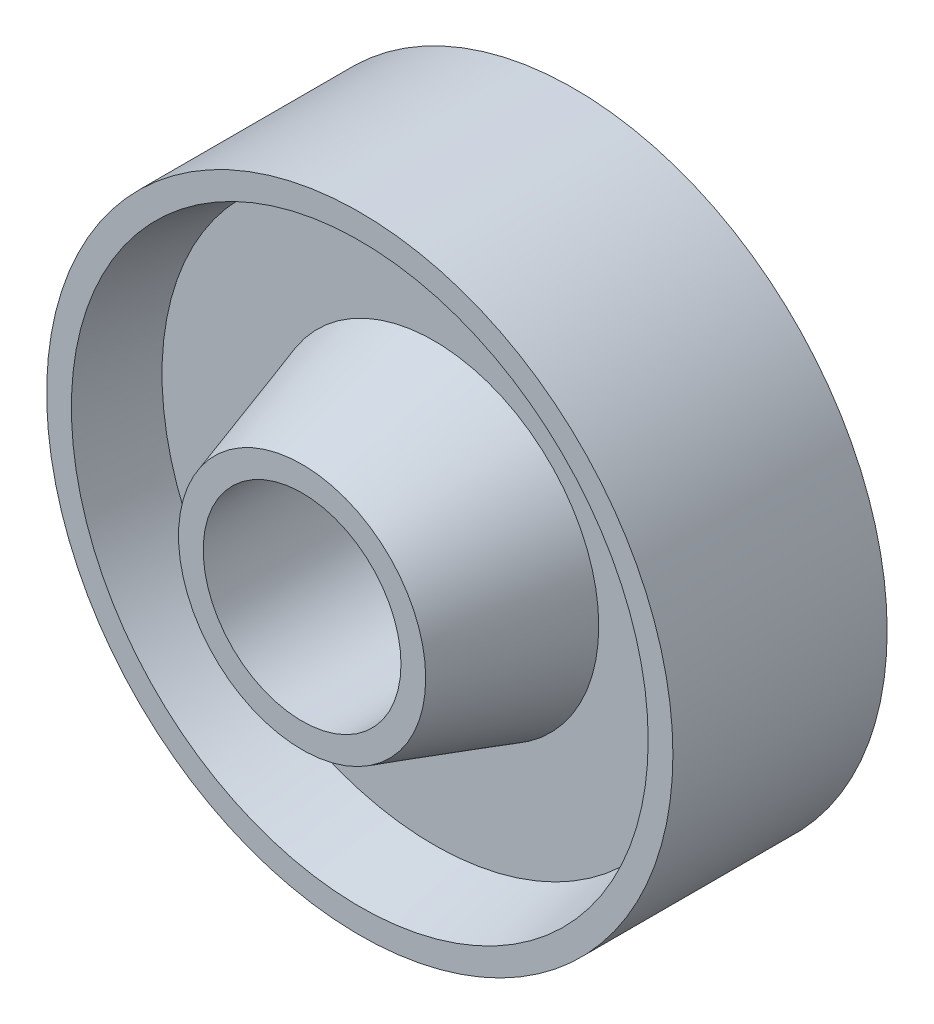
SolidWorks part; units mm, degrees
ref_plane "Front Plane" through (0, 0, 0) normal (0, 0, 1) x (1, 0, 0)
ref_plane "Top Plane" through (0, 0, 0) normal (0, 1, 0) x (1, 0, 0)
ref_plane "Right Plane" through (0, 0, 0) normal (1, 0, 0) x (0, 0, -1)
sketch "Sketch1" plane through (0, 0, 0) normal (1, 0, 0) x (0, 0, -1)
  line L0 (13, 38) -> (13, 35)
  line L1 (13, 35) -> (4, 33)
  line L2 (4, 33) -> (4, 20)
  line L3 (4, 20) -> (20, 15)
  line L4 (20, 15) -> (20, 12)
  line L5 (0, 55) -> (0, -55) construction
  line L6 (-20, 15) -> (-20, 12)
  line L7 (-4, 20) -> (-20, 15)
  line L8 (-4, 33) -> (-4, 20)
  line L9 (-13, 35) -> (-4, 33)
  line L10 (-13, 38) -> (-13, 35)
  line L11 (-13, 38) -> (13, 38)
  line L12 (-20, 12) -> (20, 12)
  line L13 (0, 0) -> (26.0146, 0) construction
  dimension "D1" = 12
  dimension "D2" = 8
  dimension "D3" = 15
  dimension "D4" = 20
  dimension "D5" = 33
  dimension "D6" = 35
  dimension "D7" = 38
  dimension "D8" = 26
  dimension "D9" = 40
revolve "Revolve1" add sketch "Sketch1" angle 360 about L13
